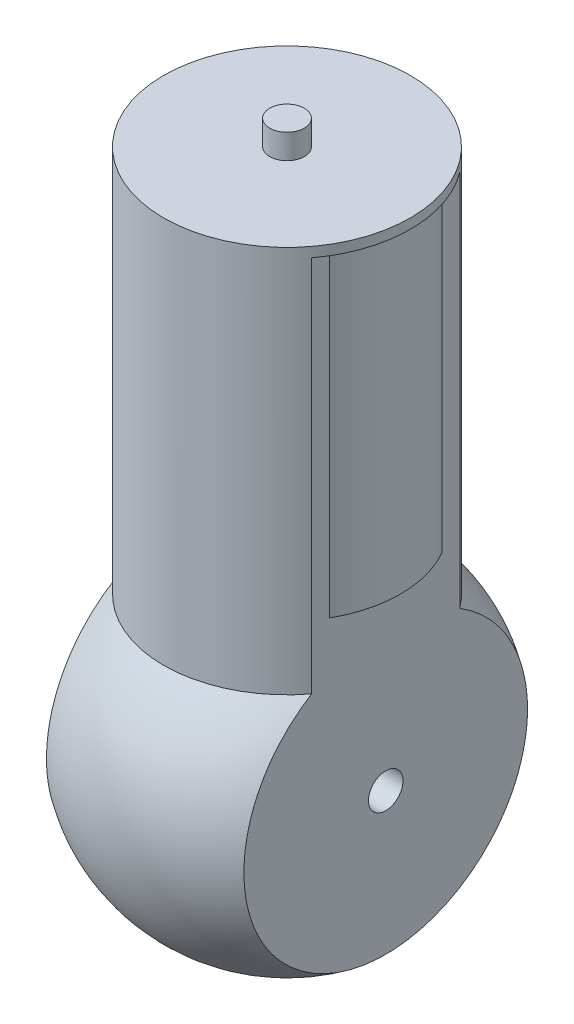
SolidWorks part; units mm, degrees
ref_plane "Front Plane" through (0, 0, 0) normal (0, 0, 1) x (1, 0, 0)
ref_plane "Top Plane" through (0, 0, 0) normal (0, 1, 0) x (1, 0, 0)
ref_plane "Right Plane" through (0, 0, 0) normal (1, 0, 0) x (0, 0, -1)
sketch "Sketch1" plane through (0, 0, 0) normal (0, 1, 0) x (1, 0, 0)
  line L0 (0, 35) -> (0, -35) construction
  line L1 (0, 35) -> (0, -35)
  arc A0 (0, -35) -> (0, 35) centre (0, 0) ccw
  dimension "D1" = 70
revolve "Revolve2" add sketch "Sketch1" angle 360 about L0
sketch "Sketch2" plane through (0, 0, 0) normal (0, 1, 0) x (1, 0, 0)
  line L2 (-20, -28.7228) -> (-20, 28.7228)
  line L4 (20, -28.7228) -> (20, 28.7228)
  line L5 (-20, -35) -> (20, 35) construction
  line L6 (-20, 35) -> (20, -35) construction
  arc A0 (20, 28.7228) -> (-20, 28.7228) centre (0, 0) ccw
  arc A1 (-20, -28.7228) -> (20, -28.7228) centre (0, 0) ccw
  dimension "D1" = 40
extrude "Cut-Extrude1" cut sketch "Sketch2" against normal up to next and the other way up to next flip side to cut
sketch "Sketch3" plane through (0, 0, 0) normal (0, 1, 0) x (1, 0, 0)
  line L4 (20, -28.7228) -> (20, 28.7228) construction
  line L6 (-20, 15) -> (-20, -15)
  line L8 (20, 15) -> (20, -15)
  line L9 (-20, 26.2775) -> (20, -26.2775) construction
  line L10 (-20, -26.2775) -> (20, 26.2775) construction
  arc A3 (20, 15) -> (-20, 15) centre (0, 0) ccw
  arc A4 (-20, -15) -> (20, -15) centre (0, 0) ccw
  arc A6 (-20, -28.7228) -> (20, -28.7228) centre (0, 0) ccw construction
  dimension "D1" = 50
  dimension "D2" = 10
extrude "Boss-Extrude1" add sketch "Sketch3" along normal blind 36
sketch "Sketch4" plane through (-20, 0, 0) normal (-1, 0, 0) x (0, 0, 1)
  circle A0 centre (0, 0) radius 3.5
  dimension "D1" = 7
extrude "Cut-Extrude2" cut sketch "Sketch4" against normal blind 5
pattern_linear "LPattern1" count 2 spacing 35 along (1, 0, 0) of "Cut-Extrude2"
sketch "Sketch5" plane through (0, 36, 0) normal (0, 1, 0) x (1, 0, 0)
  line L0 (-20, 15) -> (-20, 11.3578)
  line L1 (-20, 15) -> (-20, -15) construction
  line L2 (-20, -15) -> (-20, -11.3578)
  line L3 (20, 15) -> (20, 11.3578)
  line L4 (20, -11.3578) -> (20, -15)
  arc A0 (-20, -15) -> (20, -15) centre (0, 0) ccw
  arc A1 (20, -11.3578) -> (20, 11.3578) centre (0, 0) ccw
  arc A2 (20, 15) -> (-20, 15) centre (0, 0) ccw
  arc A3 (-20, 11.3578) -> (-20, -11.3578) centre (0, 0) ccw
  dimension "D2" = 46
extrude "Boss-Extrude2" add sketch "Sketch5" along normal blind 50
sketch "Sketch9" plane through (0, 86, 0) normal (0, 1, 0) x (1, 0, 0)
  line L4 (20, 11.3578) -> (20, 15)
  line L5 (-20, 15) -> (-20, 11.3578)
  line L6 (-20, -11.3578) -> (-20, -15)
  line L7 (20, -15) -> (20, -11.3578)
  line L8 (20, 11.3578) -> (20, 15)
  line L9 (-20, 15) -> (-20, 11.3578)
  line L10 (-20, -11.3578) -> (-20, -15)
  line L11 (20, -15) -> (20, -11.3578)
  arc A4 (20, -11.3578) -> (20, 11.3578) centre (0, 0) ccw
  arc A5 (20, 15) -> (-20, 15) centre (0, 0) ccw
  arc A6 (-20, 11.3578) -> (-20, -11.3578) centre (0, 0) ccw
  arc A7 (-20, -15) -> (20, -15) centre (0, 0) ccw
  arc A8 (20, -11.3578) -> (20, 11.3578) centre (0, 0) ccw
  arc A9 (20, 15) -> (-20, 15) centre (0, 0) ccw
  arc A10 (-20, 11.3578) -> (-20, -11.3578) centre (0, 0) ccw
  arc A11 (-20, -15) -> (20, -15) centre (0, 0) ccw
  dimension "D1" = 0
extrude "Boss-Extrude6" add sketch "Sketch9" along normal blind 15
sketch "Sketch10" plane through (0, 101, 0) normal (0, 1, 0) x (1, 0, 0)
  circle A0 centre (0, 0) radius 25
  dimension "D1" = 50
extrude "Boss-Extrude7" add sketch "Sketch10" along normal blind 2
sketch "Sketch11" plane through (0, 103, 0) normal (0, 1, 0) x (1, 0, 0)
  circle A0 centre (0, 0) radius 3.5
  dimension "D1" = 7
extrude "Boss-Extrude8" add sketch "Sketch11" along normal blind 5
